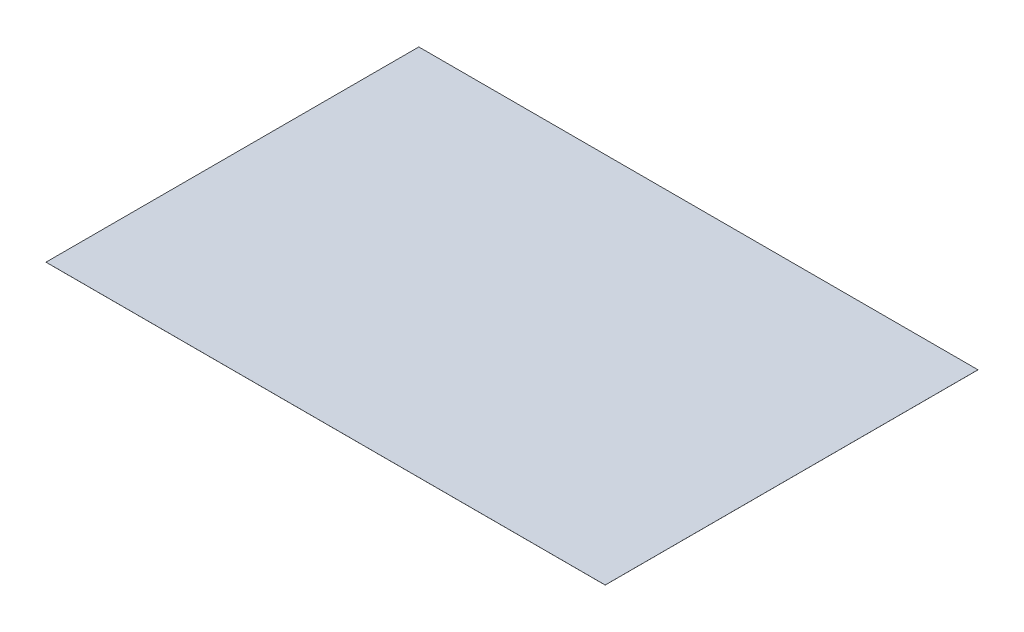
SolidWorks part; units mm, degrees
ref_plane "Alzado" through (0, 0, 0) normal (0, 0, 1) x (1, 0, 0)
ref_plane "Planta" through (0, 0, 0) normal (0, 1, 0) x (1, 0, 0)
ref_plane "Vista lateral" through (0, 0, 0) normal (1, 0, 0) x (0, 0, -1)
sketch "Croquis1" plane through (0, 0, 0) normal (0, 1, 0) x (1, 0, 0)
  line L1 (-300, 200) -> (300, 200)
  line L2 (-300, 200) -> (-300, -200)
  line L3 (-300, -200) -> (300, -200)
  line L4 (300, 200) -> (300, -200)
  line L5 (-300, 200) -> (300, -200) construction
  line L6 (-300, -200) -> (300, 200) construction
  point P0 (0, 0)
  dimension "D1" = 400
  dimension "D2" = 600
extrude "Saliente-Extruir1" add sketch "Croquis1" along normal blind 0.05
